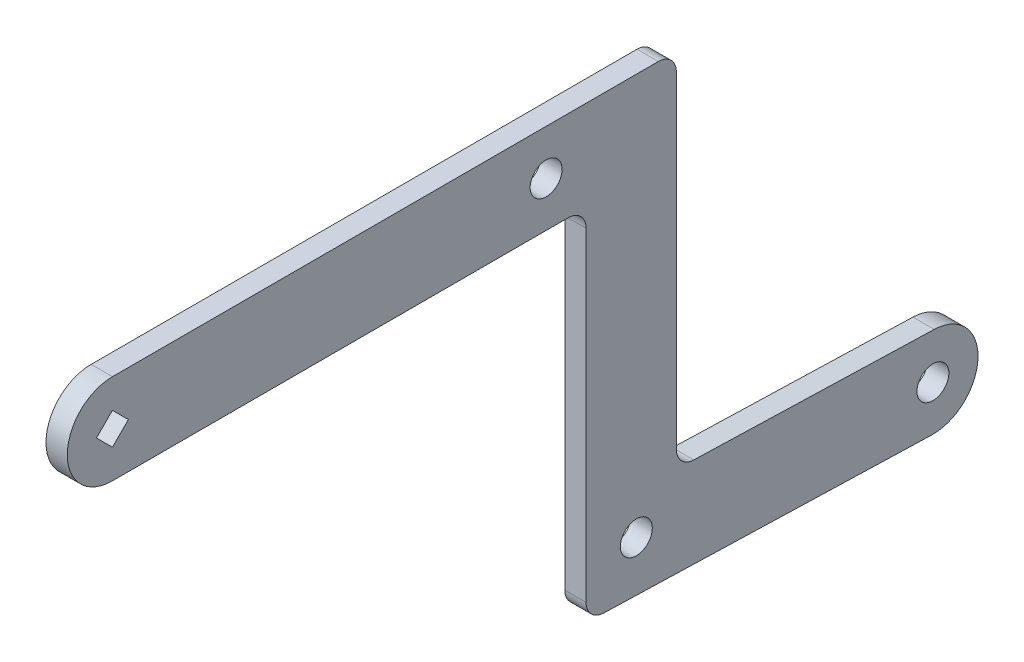
SolidWorks part; units mm, degrees
material "Custom Plastic"
ref_plane "Front Plane" through (0, 0, 0) normal (0, 0, 1) x (1, 0, 0)
ref_plane "Top Plane" through (0, 0, 0) normal (0, 1, 0) x (1, 0, 0)
ref_plane "Right Plane" through (0, 0, 0) normal (1, 0, 0) x (0, 0, -1)
sketch "Sketch1" plane through (0, 0, 0) normal (1, 0, 0) x (0, 0, -1)
  line L0 (115.4867, -52.07) -> (0, 0) construction
  line L1 (0, 0) -> (79.375, 0) construction
  line L2 (0, 2.2451) -> (2.2451, 0)
  line L3 (0, 2.2451) -> (-2.2451, 0)
  line L4 (-2.2451, 0) -> (0, -2.2451)
  line L5 (2.2451, 0) -> (0, -2.2451)
  line L6 (0, 2.2451) -> (0, -2.2451) construction
  line L7 (-2.2451, 0) -> (2.2451, 0) construction
  line L8 (117.7317, -52.07) -> (115.4867, -54.3151) construction
  line L9 (117.7317, -52.07) -> (115.4867, -49.8249) construction
  line L10 (115.4867, -49.8249) -> (113.2416, -52.07) construction
  line L11 (115.4867, -54.3151) -> (113.2416, -52.07) construction
  line L12 (117.7317, -52.07) -> (113.2416, -52.07) construction
  line L13 (115.4867, -49.8249) -> (115.4867, -54.3151) construction
  line L14 (115.6765, -45.7228) -> (115.2968, -58.4172) construction
  line L15 (0, -6.35) -> (66.675, -6.35)
  line L16 (66.675, -6.35) -> (66.675, -56.9629)
  line L17 (79.375, -44.6371) -> (66.675, -56.9629) construction
  line L18 (79.375, 6.35) -> (79.375, -44.6371)
  line L19 (79.375, 6.35) -> (0, 6.35)
  line L20 (0, -6.35) -> (0, 6.35) construction
  line L22 (66.675, -56.9629) -> (115.2968, -58.4172)
  line L24 (115.6765, -45.7228) -> (79.375, -44.6371)
  line L25 (66.675, -21.6825) -> (79.375, -21.6825) construction
  circle A0 centre (115.4867, -52.07) radius 2.2451
  arc A1 (0, 6.35) -> (0, -6.35) centre (0, 0) ccw
  arc A2 (115.6765, -45.7228) -> (115.2968, -58.4172) centre (115.4867, -52.07) cw
  point P17 (73.025, -50.8)
  dimension "D6" = 50.8
  dimension "D5" = 52.07
  dimension "D1" = 126.6825
  dimension "D2" = 3.175
  dimension "D3" = 66.675
  dimension "D4" = 6.35
extrude "Boss-Extrude1" add sketch "Sketch1" along normal blind 3
fillet "Fillet1" radius 2.54 4 edges at (1.5, -44.6371, -79.375) (1.5, 6.35, -79.375) (1.5, -56.9629, -66.675) (1.5, -6.35, -66.675)
sketch "Sketch2" plane through (3, 0, 0) normal (1, 0, 0) x (0, 0, -1)
  line L0 (80.0923, -43.9409) -> (67.3923, -56.2667) construction
  line L1 (61.0423, 6.35) -> (61.0423, -6.35) construction
  line L2 (76.835, 6.35) -> (0, 6.35) construction
  line L3 (0, -6.35) -> (64.135, -6.35) construction
  arc A0 (79.375, -42.1719) -> (81.8391, -44.7108) centre (81.915, -42.1719) ccw construction
  arc A3 (66.675, -54.4977) -> (69.1391, -57.0366) centre (69.215, -54.4977) ccw construction
  circle A4 centre (73.7423, -50.1038) radius 2.2479
  circle A5 centre (61.0423, 0) radius 2.2479
  dimension "D1" = 4.4958
  dimension "D2" = 12.7
extrude "Torque prevention" cut sketch "Sketch2" against normal through all
